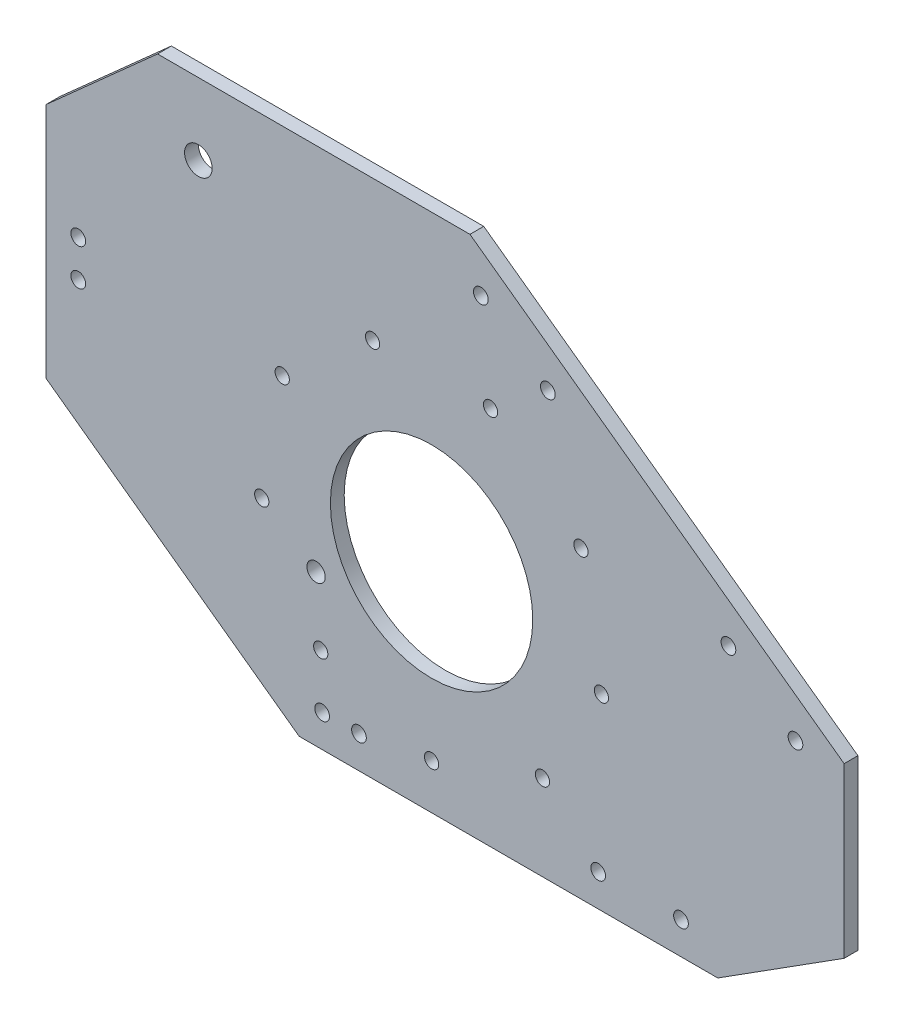
SolidWorks part; units mm, degrees
material "3240环氧板"
ref_plane "前视基准面" through (0, 0, 0) normal (0, 0, 1) x (1, 0, 0)
ref_plane "上视基准面" through (0, 0, 0) normal (0, 1, 0) x (1, 0, 0)
ref_plane "右视基准面" through (0, 0, 0) normal (1, 0, 0) x (0, 0, -1)
other "Configuration Table"
sketch "草图1" plane through (0, 0, -47.1117) normal (0, 0, -1) x (-1, 0, 0)
  line L0 (-65.205, 2.2592) -> (25.8155, 2.2592)
  line L1 (-11.3221, 115.3599) -> (56.6007, 115.3599)
  line L2 (-92.6857, 56.3647) -> (-92.6857, 19.6988)
  line L4 (80.8481, 93.7183) -> (80.8481, 42.1397)
  line L5 (-95.0713, 200.9129) -> (89.1178, -101.7657) construction
  line L6 (-163.2602, -70.2134) -> (134.2149, 152.1031) construction
  line L9 (-92.6857, 19.6988) -> (-65.205, 2.2592)
  line L11 (-11.3221, 115.3599) -> (-92.6857, 56.3647)
  line L12 (25.8155, 2.2592) -> (80.8481, 42.1397)
  line L13 (56.6007, 115.3599) -> (80.8481, 93.7183)
  circle A0 centre (-2.9768, 49.5736) radius 22
  circle A1 centre (22.1383, 35.0742) radius 2
  point P0 (-2.9768, 49.5736)
extrude "凸台-拉伸1" add sketch "草图1" along normal blind 3
sketch "草图2" plane through (0, 0, -50.1117) normal (0, 0, -1) x (-1, 0, 0)
  line L0 (-2.9768, 49.5736) -> (47.7332, 49.5736) construction
  line L1 (47.7332, 49.5736) -> (47.7332, 99.7336) construction
  circle A0 centre (47.7332, 99.7336) radius 3
  dimension "D3" = 6
  dimension "D1" = 50.71
  dimension "D2" = 50.16
extrude "切除-拉伸1" cut sketch "草图2" against normal blind 3 contours A0
sketch "草图4" plane through (0, 0, -50.1117) normal (0, 0, -1) x (-1, 0, 0)
  circle A0 centre (21.1278, 20.8469) radius 1.5503
  circle A1 centre (-2.9768, 12.0736) radius 1.5503
  circle A2 centre (-27.0813, 20.8469) radius 1.5503
  circle A3 centre (-39.9071, 43.0618) radius 1.5503
  circle A4 centre (-35.4527, 68.3236) radius 1.5503
  circle A5 centre (-15.8025, 84.8121) radius 1.5503
  circle A6 centre (9.849, 84.8121) radius 1.5503
  circle A7 centre (29.4992, 68.3236) radius 1.5503
  circle A8 centre (33.9537, 43.0628) radius 1.5503
  circle A9 centre (-57.205, 9.2592) radius 1.6
  circle A10 centre (-39.205, 9.2592) radius 1.6
  dimension "D1" = 3.2
  dimension "D2" = 3.2
extrude "切除-拉伸2" cut sketch "草图4" against normal blind 3
sketch "草图5" plane through (0, 0, -50.1117) normal (0, 0, -1) x (-1, 0, 0)
  circle A0 centre (73.8481, 72.2183) radius 1.6
  circle A1 centre (73.8481, 64.2183) radius 1.6
  dimension "D1" = 3.2
  dimension "D2" = 3.2
extrude "切除-拉伸3" cut sketch "草图5" against normal blind 3
sketch "草图6" plane through (0, 0, -50.1117) normal (0, 0, -1) x (-1, 0, 0)
  circle A0 centre (-82.0999, 55.3937) radius 1.6
  circle A1 centre (-67.5275, 65.9599) radius 1.6
  circle A2 centre (-28.2621, 94.4305) radius 1.6
  circle A3 centre (-13.6896, 104.9967) radius 1.6
  dimension "D1" = 3.2
  dimension "D2" = 3.2
  dimension "D3" = 3.2
  dimension "D4" = 3.2
extrude "切除-拉伸4" cut sketch "草图6" against normal blind 3
sketch "草图7" plane through (0, 0, -50.1117) normal (0, 0, -1) x (-1, 0, 0)
  circle A0 centre (12.8155, 9.2592) radius 1.6
  circle A1 centre (20.8155, 9.2592) radius 1.6
  dimension "D1" = 3.2
  dimension "D2" = 3.2
extrude "切除-拉伸7" cut sketch "草图7" against normal through all
